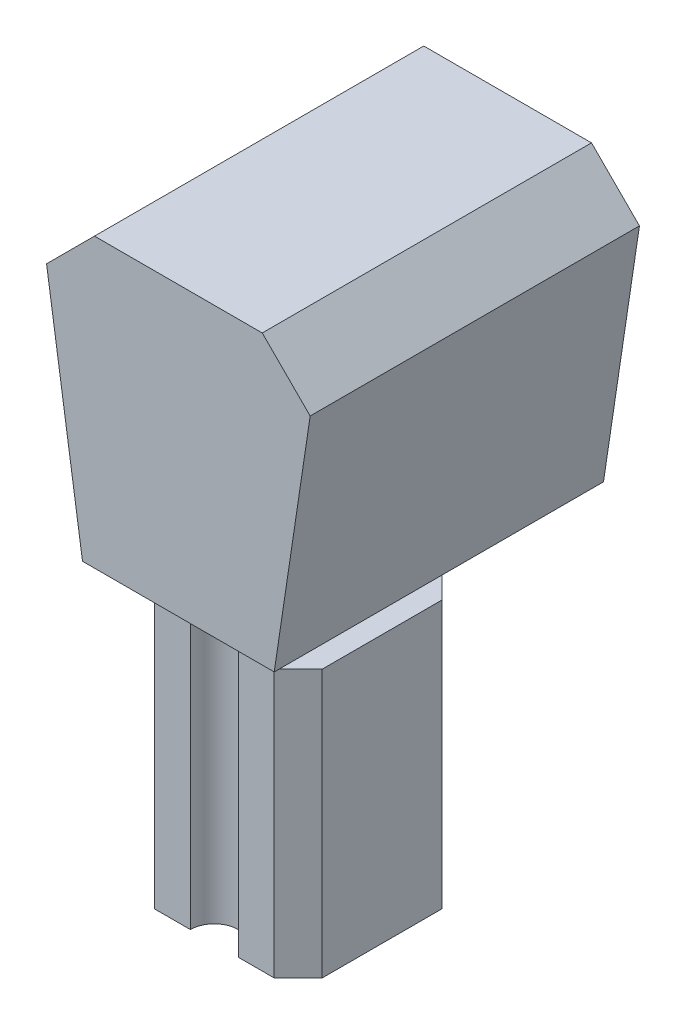
SolidWorks part; units mm, degrees
ref_plane "Plano frontal" through (0, 0, 0) normal (0, 0, 1) x (1, 0, 0)
ref_plane "Plano superior" through (0, 0, 0) normal (0, 1, 0) x (1, 0, 0)
ref_plane "Plano direito" through (0, 0, 0) normal (1, 0, 0) x (0, 0, -1)
ref_plane "CHÃO" through (0, 0, 75) normal (0, 0, 1) x (1, 0, 0)
sketch "Esboço8" plane through (0, 0, 75) normal (0, 0, 1) x (1, 0, 0)
  line L0 (-644.8309, 0) -> (603.2318, 0)
  line L4 (0, 528.1567) -> (0, -481.6028)
ref_plane "FH" through (0, 0, 0) normal (0, 1, 0) x (1, 0, 0)
ref_plane "MH" through (0, 740, 0) normal (0, 1, 0) x (1, 0, 0)
ref_plane "FBH" through (0, -680, 0) normal (0, 1, 0) x (1, 0, 0)
ref_plane "RBH" through (0, 1430, 0) normal (0, 1, 0) x (1, 0, 0)
sketch "linha ref" plane through (0, 740, 0) normal (0, 1, 0) x (1, 0, 0)
  line L0 (-79.716, 0) -> (79.716, 0) construction
ref_plane "MH°" through (0, 734.3789, 64.2498) normal (0, 0.9962, 0.0872) x (1, 0, 0)
sketch "front hoop" plane through (0, 0, 0) normal (0, 1, 0) x (1, 0, 0)
  line L0 (-200079.716, 0) -> (200079.716, 0) construction
  line L3 (200, 42) -> (-200, 42) construction
  dimension "D1" = 42
sketch "front bulkhead" plane through (0, -680, 0) normal (0, 1, 0) x (1, 0, 0)
  line L0 (-55, -75) -> (55, -75) construction
  line L1 (-175, 75) -> (175, 75)
  line L2 (-175, 75) -> (-175, 425)
  line L3 (-175, 425) -> (175, 425)
  line L4 (175, 75) -> (175, 425)
  line L5 (-175, 75) -> (175, 425) construction
  line L6 (-175, 425) -> (175, 75) construction
  line L7 (-175, 425) -> (175, 75)
  point P0 (0, 250)
  dimension "D1" = 350
  dimension "D2" = 150
sketch "Esboço6" plane through (0, 0, 0) normal (0, 0, 1) x (1, 0, 0)
  line L0 (-200, 70) -> (200, 70)
  line L1 (200, 70) -> (275, 570)
  line L2 (275, 570) -> (175, 670)
  line L3 (175, 670) -> (-175, 670)
  line L4 (-175, 670) -> (-275, 570)
  line L5 (-275, 570) -> (-200, 70)
  point P9 (0, 670)
  dimension "D1" = 100
  dimension "D2" = 600
  dimension "D3" = 100
  dimension "D4" = 400
  dimension "D5" = 350
  dimension "D6" = 70
extrude "Ressalto-extrusão1" add sketch "Esboço6" against normal blind 687 contours L5 L0 L1 L2 L3 L4
ref_plane "FH°" through (0, 2.1951, -0.115) normal (0, 0.9986, -0.0523) x (-1, 0, 0)
sketch3d "PSD"
  line L0 (-255, 0, -42.383) -> (-255, -240.84, -42.383) construction
  line L1 (-255, -240.84, -42.383) -> (-255, -240.84, -254.503) construction
  line L2 (-255, -240.84, -254.503) -> (-255, 0, -254.503) construction
  line L4 (-205, -240.84, -254.503) -> (-205, -240.84, -42.383) construction
  line L5 (-205, -240.84, -42.383) -> (-255, -240.84, -42.383) construction
  line L6 (-205, 0, -254.503) -> (-205, 0, -42.383) construction
  line L7 (-205, -240.84, -42.383) -> (-205, 0, -42.383)
  line L8 (-255, 0, -42.383) -> (-255, 0, -254.503) construction
  line L9 (-205, 0, -42.383) -> (-255, 0, -42.383) construction
  line L11 (-255, 0, -254.503) -> (-205, 0, -254.503) construction
  line L12 (-205, 0, -254.503) -> (-205, -240.84, -254.503) construction
  line L13 (-255, -240.84, -254.503) -> (-205, -240.84, -254.503) construction
  line L14 (-205, -240.84, -42.383) -> (-255, -221.47, -254.503)
  line L16 (-255, -221.47, -254.503) -> (-255, -14.5, -254.503) construction
  line L17 (-255, -14.5, -254.503) -> (-255, -14.5, -244.753) construction
  line L18 (-255, -14.5, -244.753) -> (-205, 0, -42.383)
  line L19 (-255, -221.47, -254.503) -> (-255, -14.5, -244.753)
  line L20 (255, -14.5, -254.503) -> (255, -14.5, -244.753) construction
  line L21 (255, -221.47, -254.503) -> (255, -14.5, -254.503) construction
  line L22 (255, -240.84, -254.503) -> (205, -240.84, -254.503) construction
  line L23 (205, 0, -254.503) -> (205, -240.84, -254.503) construction
  line L24 (255, 0, -254.503) -> (205, 0, -254.503) construction
  line L25 (205, 0, -42.383) -> (255, 0, -42.383) construction
  line L26 (255, 0, -42.383) -> (255, 0, -254.503) construction
  line L27 (205, 0, -254.503) -> (205, 0, -42.383) construction
  line L28 (205, -240.84, -42.383) -> (255, -240.84, -42.383) construction
  line L29 (205, -240.84, -254.503) -> (205, -240.84, -42.383) construction
  line L30 (255, -240.84, -254.503) -> (255, 0, -254.503) construction
  line L31 (255, -240.84, -42.383) -> (255, -240.84, -254.503) construction
  line L32 (255, 0, -42.383) -> (255, -240.84, -42.383) construction
  line L33 (255, -221.47, -254.503) -> (255, -14.5, -244.753)
  line L34 (255, -14.5, -244.753) -> (205, 0, -42.383)
  line L35 (205, -240.84, -42.383) -> (255, -221.47, -254.503)
  line L36 (205, -240.84, -42.383) -> (205, 0, -42.383)
  line L37 (-205, 0, -42.383) -> (205, 0, -42.383)
  point P5 (0, 0, -42.383)
  point P6 (-255, -212.8951, -42.383)
  point P9 (-255, -240.84, -260.5901)
  dimension "D1" = 50
  dimension "D2" = 9.75
  dimension "D3" = 14.5
  dimension "D5" = 19.37
  dimension "D4" = 240.84
  dimension "D6" = 212.12
  dimension "D7" = 410
  dimension "D8" = 117.383
sketch "MH esb" plane through (0, 734.3789, 64.2498) normal (0, 0.9962, 0.0872) x (1, 0, 0)
  line L0 (-230, 21.3173) -> (-344.8215, 313.2916)
  line L1 (-230, 21.3173) -> (230, 21.3173)
  line L5 (0, 21.3173) -> (0, 1121.3173) construction
  line L7 (230, 21.3173) -> (344.8215, 313.2916)
  line L8 (346.1365, 364.5749) -> (116, 1051.186)
  line L9 (-116, 1051.186) -> (-346.1365, 364.5749)
  arc A0 (116, 1051.186) -> (-116, 1051.186) centre (0, 990.3173) ccw
  arc A1 (-344.8215, 313.2916) -> (-346.1365, 364.5749) centre (-275.0246, 340.7398) cw
  arc A2 (344.8215, 313.2916) -> (346.1365, 364.5749) centre (275.0246, 340.7398) ccw
  point P5 (350, 338.8173)
  point P9 (-350, 338.8173)
  point P10 (0, 1121.3173)
  point P11 (0, 21.3173)
  point P12 (0, 0)
  point P18 (-354.8112, 338.6939)
  point P21 (354.8112, 338.6939)
  dimension "D1" = 460
  dimension "D2" = 75
  dimension "D3" = 1100
  dimension "D6" = 232
  dimension "D8" = 131
  dimension "D4" = 317.5
  dimension "D5" = 700
  dimension "D7" = 50
sketch3d "PST"
  line L0 (-255, 1320.3211, -53.599) -> (-255, 1120.3211, -53.599) construction
  line L1 (-175, 1120.3211, -53.599) -> (-175, 1320.3211, -53.599) construction
  line L2 (175, 1120.3211, -53.599) -> (175, 1320.3211, -53.599) construction
  line L3 (-255, 1120.3211, -53.599) -> (-255, 1120.3211, -261.859) construction
  line L4 (-255, 1120.3211, -261.859) -> (-255, 1320.3211, -261.859) construction
  line L5 (-255, 1120.3211, -53.599) -> (-255, 1120.3211, -261.859) construction
  line L6 (-255, 1320.3211, -53.599) -> (-255, 1320.3211, -261.859) construction
  line L7 (-255, 1320.3211, -261.859) -> (-175, 1320.3211, -261.859) construction
  line L8 (-175, 1320.3211, -261.859) -> (-175, 1320.3211, -53.599) construction
  line L9 (-175, 1320.3211, -53.599) -> (-255, 1320.3211, -53.599) construction
  line L10 (-175, 1320.3211, -261.859) -> (-175, 1120.3211, -261.859) construction
  line L11 (-175, 1120.3211, -261.859) -> (-255, 1120.3211, -261.859) construction
  line L12 (-255, 1120.3211, -53.599) -> (-175, 1120.3211, -53.599) construction
  line L14 (-175, 1120.3211, -261.859) -> (-175, 1120.3211, -53.599) construction
  line L18 (-255, 1215.1911, -261.859) -> (-210, 1340.3211, -252.929)
  line L19 (-255, 0, -42.383) -> (-255, -240.84, -42.383) construction
  line L20 (-255, 0, -42.383) -> (-255, -240.84, -42.383) construction
  line L21 (-255, 0, -42.383) -> (-255, -120.42, -42.383) construction
  line L22 (175, 1120.3211, -261.859) -> (175, 1120.3211, -53.599) construction
  line L23 (255, 1120.3211, -53.599) -> (175, 1120.3211, -53.599) construction
  line L24 (175, 1120.3211, -261.859) -> (255, 1120.3211, -261.859) construction
  line L25 (175, 1320.3211, -261.859) -> (175, 1120.3211, -261.859) construction
  line L26 (175, 1320.3211, -53.599) -> (255, 1320.3211, -53.599) construction
  line L27 (175, 1320.3211, -261.859) -> (175, 1320.3211, -53.599) construction
  line L28 (255, 1320.3211, -261.859) -> (175, 1320.3211, -261.859) construction
  line L29 (255, 1320.3211, -53.599) -> (255, 1320.3211, -261.859) construction
  line L30 (255, 1120.3211, -53.599) -> (255, 1120.3211, -261.859) construction
  line L31 (255, 1120.3211, -261.859) -> (255, 1320.3211, -261.859) construction
  line L32 (255, 1120.3211, -53.599) -> (255, 1120.3211, -261.859) construction
  line L33 (255, 1320.3211, -53.599) -> (255, 1120.3211, -53.599) construction
  line L38 (-175, 1320.3211, -53.599) -> (175, 1320.3211, -53.599) construction
  line L39 (-255, 1215.1911, -261.859) -> (-215, 1151.6011, -53.649)
  line L40 (-255, 1215.1911, -261.859) -> (-210, 1215.1911, -261.859) construction
  line L41 (-210, 1215.1911, -261.859) -> (-210, 1340.3211, -261.859) construction
  line L42 (-210, 1340.3211, -261.859) -> (-210, 1340.3211, -252.929) construction
  line L43 (-210, 1340.3211, -252.929) -> (-175, 1320.3211, -53.599)
  line L44 (-175, 1151.6011, -53.599) -> (-175, 1151.6011, -53.649) construction
  line L45 (-175, 1151.6011, -53.649) -> (-215, 1151.6011, -53.649) construction
  line L46 (-215, 1151.6011, -53.649) -> (-175, 1320.3211, -53.599)
  line L47 (210, 1340.3211, -252.929) -> (175, 1320.3211, -53.599)
  line L48 (255, 1215.1911, -261.859) -> (210, 1340.3211, -252.929)
  line L49 (255, 1215.1911, -261.859) -> (215, 1151.6011, -53.649)
  line L50 (215, 1151.6011, -53.649) -> (175, 1320.3211, -53.599)
  point P2 (0, 1320.3211, -53.599)
  point P31 (0, 0, 0)
  point P33 (-255, -14.5, -244.753)
  point P37 (0, 0, 0)
  point P39 (0, 0, 0)
  dimension "D4" = 94.87
  dimension "D1" = 208.26
  dimension "D2" = 80
  dimension "D3" = 200
  dimension "D5" = 45
  dimension "D7" = 8.93
  dimension "D6" = 125.13
  dimension "D9" = 128.599
  dimension "D8" = 350
  dimension "D10" = 0.05
  dimension "D11" = 168.72
  dimension "D12" = 40
  dimension "D13" = 1134.95
ref_plane "Plano5" through (0, 3.0213, -0.2165) normal (0, -0.9974, 0.0715) x (-1, 0, 0)
sketch "Esboço7" plane through (0, 1.8651, -16.3522) normal (0, -0.9974, 0.0715) x (-1, 0, 0)
  line L3 (245.3808, 252.2973) -> (156.1781, 468.4689)
  line L7 (-245.3808, 252.2973) -> (-156.1781, 468.4689)
  line L8 (-255, 228.9863) -> (-205, 26.0975) construction
  line L9 (-248.9659, 204.5012) -> (-205, 26.0975)
  line L10 (205, 26.0975) -> (-205, 26.0975) construction
  line L11 (205, 26.0975) -> (-205, 26.0975)
  line L12 (255, 228.9863) -> (205, 26.0975) construction
  line L13 (248.9659, 204.5012) -> (205, 26.0975)
  line L15 (85, 516.0975) -> (-85, 516.0975)
  line L16 (0, 38.8229) -> (0, -71.1771) construction
  arc A4 (-156.1781, 468.4689) -> (-85, 516.0975) centre (-85, 439.0975) cw
  arc A5 (156.1781, 468.4689) -> (85, 516.0975) centre (85, 439.0975) ccw
  arc A6 (248.9659, 204.5012) -> (245.3808, 252.2973) centre (174.2027, 222.9258) ccw
  arc A7 (-248.9659, 204.5012) -> (-245.3808, 252.2973) centre (-174.2027, 222.9258) cw
  point P9 (0, 516.0975)
  dimension "D1" = 77
  dimension "D4" = 77
  dimension "D2" = 170
  dimension "D3" = 490
sketch3d "Tri_Frente"
  line L0 (-205, -240.84, -42.383) -> (-175, -680, -75)
  line L1 (205, -240.84, -42.383) -> (175, -680, -75)
  line L2 (175, -680, -75) -> (255, -221.47, -254.503)
  line L3 (-175, -680, -425) -> (-152.983, -32.1002, -490.3913)
  line L4 (-255, -221.47, -254.503) -> (-152.983, -32.1002, -490.3913)
  line L5 (-255, -221.47, -254.503) -> (-175, -680, -425)
  line L8 (-175, -680, -75) -> (-255, -221.47, -254.503)
  line L9 (255, -221.47, -254.503) -> (175, -680, -425)
  line L10 (255, -221.47, -254.503) -> (152.983, -32.1002, -490.3913)
  line L11 (175, -680, -425) -> (152.983, -32.1002, -490.3913)
  line L12 (205, -240.84, -42.383) -> (175, -680, -75)
  line L13 (205, 0, -42.383) -> (255, -221.47, -254.503)
  line L14 (-255, -221.47, -254.503) -> (-205, 0, -42.383)
  arc A0 (-156.1781, -31.6153, -483.6233) -> (-85, -35.0192, -531.13) centre (-85, -29.5162, -454.3269) ccw construction
  point P17 (-85, -106.3193, -448.8239)
  dimension "D1" = 7.5
  dimension "D2" = 7.5
sketch3d "Tri_Tras"
  line L0 (-230, 736.2368, 43.0137) -> (-215, 1151.6011, -53.649)
  line L1 (-255, 1215.1911, -261.859) -> (-350, 763.9087, -273.2782)
  line L2 (-350, 763.9087, -273.2782) -> (-215, 1151.6011, -53.649)
  line L3 (-215, 1151.6011, -53.649) -> (-210, 1340.3211, -252.929)
  line L4 (215, 1151.6011, -53.649) -> (210, 1340.3211, -252.929)
  line L5 (350, 763.9087, -273.2782) -> (215, 1151.6011, -53.649)
  line L6 (255, 1215.1911, -261.859) -> (350, 763.9087, -273.2782)
  line L7 (230, 736.2368, 43.0137) -> (215, 1151.6011, -53.649)
  line L8 (116, 825.9958, -982.9361) -> (210, 1340.3211, -252.929)
  line L9 (-210, 1340.3211, -252.929) -> (-116, 825.9958, -982.9361)
  arc A0 (-344.8215, 761.684, -247.8496) -> (-346.1365, 766.1537, -298.9377) centre (-275.0246, 764.0763, -275.1933) ccw construction
  point P19 (0, 0, 0)
  point P23 (-275.0246, 689.3617, -281.73)
  point P24 (-350, 763.9087, -273.2782)
  point P25 (0, 0, 0)
  point P27 (0, 0, 0)
  point P29 (0, 0, 0)
sketch3d "Tri_Meio"
  line L0 (-205, 0, -42.383) -> (-230, 736.2368, 43.0137)
  line L1 (-250.987, -14.4785, -244.4528) -> (-350, 763.9087, -273.2782)
  line L3 (-152.983, -32.1002, -490.3913) -> (-350, 763.9087, -273.2782)
  line L4 (-250.987, -14.4785, -244.4528) -> (-230, 736.2368, 43.0137)
  line L5 (250.987, -14.4785, -244.4528) -> (230, 736.2368, 43.0137)
  line L7 (152.983, -32.1002, -490.3913) -> (350, 763.9087, -273.2782)
  line L8 (250.987, -14.4785, -244.4528) -> (350, 763.9087, -273.2782)
  line L9 (205, 0, -42.383) -> (230, 736.2368, 43.0137)
  arc A0 (-248.9659, -12.7501, -220.3305) -> (-245.3808, -16.166, -268.0044) centre (-174.2027, -14.0669, -238.708) ccw construction
  arc A1 (-344.8215, 761.684, -247.8496) -> (-346.1365, 766.1537, -298.9377) centre (-275.0246, 764.0763, -275.1933) ccw construction
  point P2 (-245.1769, -15.4122, -267.9679)
  point P3 (0, 0, 0)
  point P5 (-249.456, -10.3518, -261.3768)
  point P9 (-379.554, 785.9855, -253.9005)
  point P18 (-174.2027, -90.87, -233.205)
  point P24 (0, 0, 0)
  point P25 (-250.987, -14.4785, -244.4528)
  point P26 (0, 0, 0)
  point P29 (-275.0246, 689.3617, -281.73)
  point P30 (-350, 763.9087, -273.2782)
sketch "Esboço9" plane through (0, 0, 0) normal (1, 0, 0) x (0, 0, -1)
  line L0 (762.2532, 706.2368) -> (482.2532, 706.2368)
  line L1 (96.1279, 404.5627) -> (482.2532, 706.2368)
  line L2 (96.1279, 404.5627) -> (96.1279, -510.4373)
  line L3 (96.1279, 404.5627) -> (255.016, -496.5364) construction
  line L4 (96.1279, 404.5627) -> (-62.7602, -496.5364) construction
  line L5 (542.0125, -41.5661) -> (1063.6829, 825.5612) construction
  line L6 (42.383, 0) -> (-43.0137, 736.2368) construction
  line L7 (931.5639, 605.9513) -> (891.4756, 630.0687)
  line L8 (1059.6112, 842.8274) -> (259.7397, 1351.0404) construction
  line L9 (875.5176, 959.7947) -> (805.6453, 849.8234)
  circle A0 centre (762.2532, 706.2368) radius 150
  circle A1 centre (482.2532, 706.2368) radius 100
  circle A2 centre (96.1279, 404.5627) radius 100
  arc A3 (-62.7602, -496.5364) -> (255.016, -496.5364) centre (96.1279, 404.5627) ccw
  circle A4 centre (531.13, -35.0192) radius 12.7
  circle A5 centre (1052.8005, 832.1081) radius 12.7
  circle A6 centre (252.929, 1340.3211) radius 12.7
  point P6 (1052.8005, 832.1081)
  point P7 (531.13, -35.0192)
  point P15 (252.929, 1340.3211)
  point P26 (0, 0)
  point P33 (0, 0)
  point P34 (252.929, 1340.3211)
  point P36 (0, 0)
  point P37 (96.0432, 456.3057)
  point P38 (260.0076, 1350.8654)
  point P39 (1040.1803, 855.8268)
  dimension "D1" = 200
  dimension "D2" = 300
  dimension "D6" = 915
  dimension "D9" = 25.4
  dimension "D10" = 30
  dimension "D3" = 38
  dimension "D4" = 280
  dimension "D5" = 490
  dimension "D7" = 10
  dimension "D8" = 10
sketch "Esboço10" plane through (0, 0, 0) normal (0, 1, 0) x (1, 0, 0)
  line L0 (-175, 375) -> (-125, 425)
  line L1 (-125, 75) -> (-50, 75)
  line L2 (-175, 125) -> (-175, 375)
  line L3 (-125, 425) -> (-50, 425)
  line L4 (175, 125) -> (175, 375)
  line L5 (-175, 75) -> (175, 425) construction
  line L6 (-175, 425) -> (175, 75) construction
  line L7 (125, 425) -> (175, 375)
  line L8 (125, 75) -> (175, 125)
  line L9 (-175, 125) -> (-125, 75)
  line L10 (50, 75) -> (125, 75)
  line L11 (50, 425) -> (125, 425)
  arc A0 (-50, 425) -> (50, 425) centre (0, 425) ccw
  arc A1 (50, 75) -> (-50, 75) centre (0, 75) ccw
  point P0 (0, 250)
  point P2 (0, 250)
  point P18 (0, 0)
  point P22 (-50, 429.5)
  point P23 (0, 0)
  point P24 (0, 0)
  dimension "D3" = 50
  dimension "D1" = 350
  dimension "D2" = 350
extrude "Ressalto-extrusão2" add sketch "Esboço10" against normal blind 558 separate body
